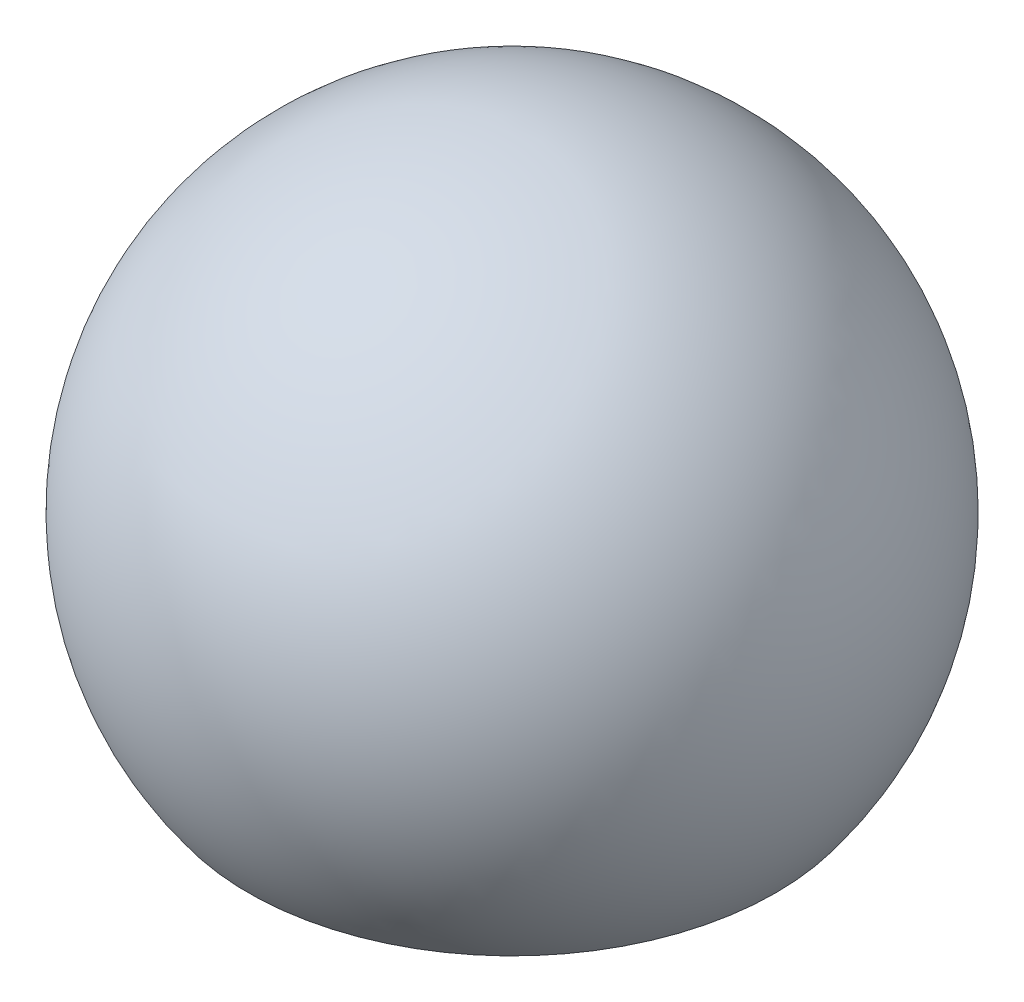
SolidWorks part; units mm, degrees
ref_plane "Front Plane" through (0, 0, 0) normal (0, 0, 1) x (1, 0, 0)
ref_plane "Top Plane" through (0, 0, 0) normal (0, 1, 0) x (1, 0, 0)
ref_plane "Right Plane" through (0, 0, 0) normal (1, 0, 0) x (0, 0, -1)
sketch "Sketch1" plane through (0, 0, 0) normal (0, 0, 1) x (1, 0, 0)
  line L0 (0, 0.25) -> (0, -0.15)
  line L1 (0, -0.15) -> (0.2, -0.15)
  arc A0 (0, 0.25) -> (0.2, -0.15) centre (0, 0) cw
  dimension "D1" = 0.2
  dimension "D2" = 0.4
revolve "Revolve1" add sketch "Sketch1" angle 360 about L0
